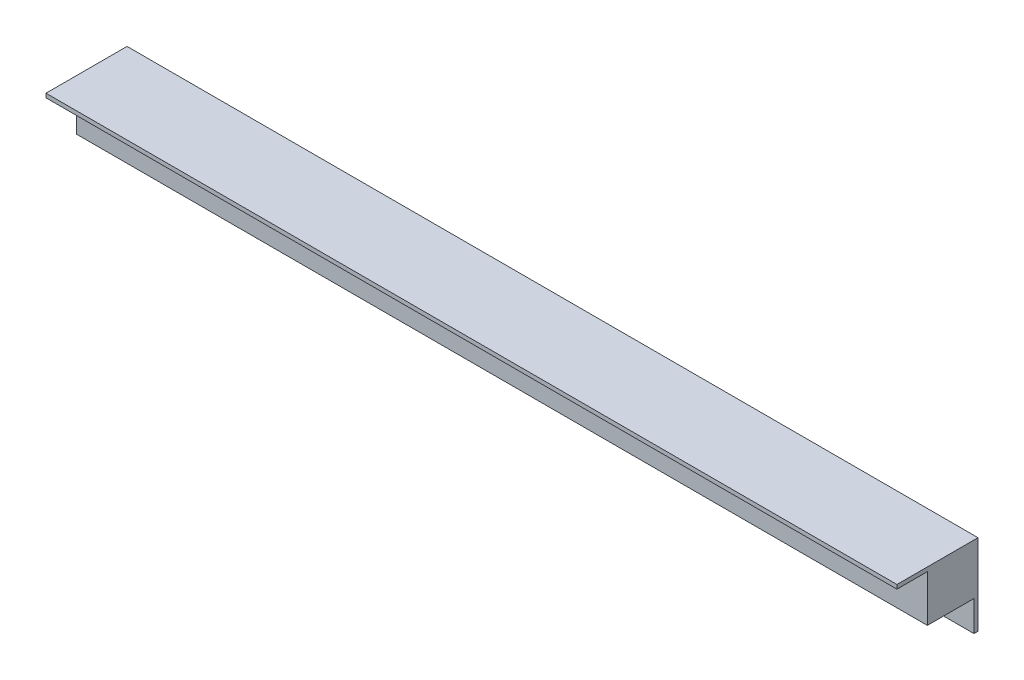
SolidWorks part; units mm, degrees
ref_plane "Front Plane" through (0, 0, 0) normal (0, 0, 1) x (1, 0, 0)
ref_plane "Top Plane" through (0, 0, 0) normal (0, 1, 0) x (1, 0, 0)
ref_plane "Right Plane" through (0, 0, 0) normal (1, 0, 0) x (0, 0, -1)
sketch "Sketch2" plane through (0, 0, 0) normal (0, 0, 1) x (1, 0, 0)
  line L1 (-216.5932, 102.7054) -> (203.4068, 102.7054)
  line L2 (-216.5932, 102.7054) -> (-216.5932, 62.7054)
  line L3 (-216.5932, 62.7054) -> (203.4068, 62.7054)
  line L4 (203.4068, 102.7054) -> (203.4068, 62.7054)
  dimension "D1" = 420
  dimension "D2" = 40
extrude "Boss-Extrude1" add sketch "Sketch2" along normal blind 40
sketch "Sketch3" plane through (-216.5932, 0, 0) normal (-1, 0, 0) x (0, 0, 1)
  line L0 (40, 102.7054) -> (0, 102.7054) construction
  line L1 (2, 100.7054) -> (40, 100.7054)
  line L2 (2, 100.7054) -> (2, 62.7054)
  line L3 (2, 62.7054) -> (40, 62.7054)
  line L4 (40, 100.7054) -> (40, 62.7054)
  line L5 (0, 102.7054) -> (0, 62.7054) construction
  line L6 (40, 102.7054) -> (40, 62.7054) construction
  line L7 (40, 62.7054) -> (0, 62.7054) construction
  dimension "D1" = 2
  dimension "D2" = 2
  dimension "D3" = 0
  dimension "D4" = 0
extrude "Cut-Extrude1" cut sketch "Sketch3" against normal blind 1000
sketch "Sketch4" plane through (-216.5932, 0, 0) normal (-1, 0, 0) x (0, 0, 1)
  line L0 (2, 100.7054) -> (2, 62.7054) construction
  line L1 (2, 100.7054) -> (25, 100.7054)
  line L2 (2, 100.7054) -> (2, 77.7054)
  line L3 (2, 77.7054) -> (25, 77.7054)
  line L4 (25, 100.7054) -> (25, 77.7054)
  line L5 (40, 100.7054) -> (2, 100.7054) construction
  line L6 (2, 62.7054) -> (0, 62.7054) construction
  line L7 (40, 102.7054) -> (40, 100.7054) construction
  dimension "D1" = 0
  dimension "D2" = 0
  dimension "D3" = 15
  dimension "D4" = 15
extrude "Boss-Extrude2" add sketch "Sketch4" against normal up to surface (420 mm away) up to face at (203.4068, 88.7054, 14)
